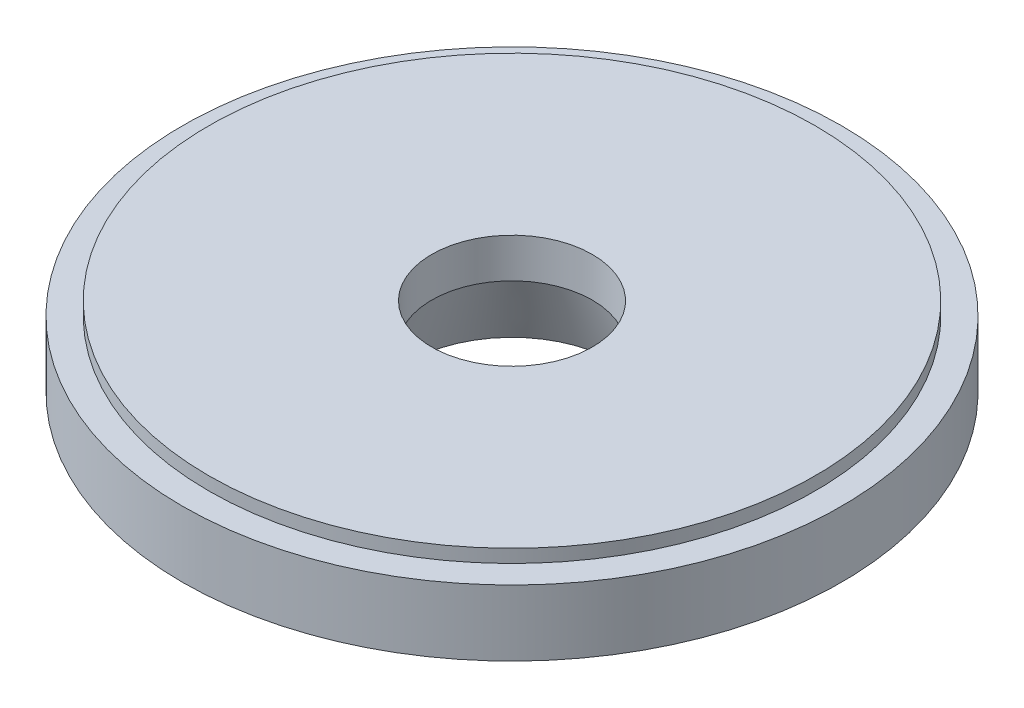
SolidWorks part; units mm, degrees
material "6061 Alloy"
ref_plane "Front Plane" through (0, 0, 0) normal (0, 0, 1) x (1, 0, 0)
ref_plane "Top Plane" through (0, 0, 0) normal (0, 1, 0) x (1, 0, 0)
ref_plane "Right Plane" through (0, 0, 0) normal (1, 0, 0) x (0, 0, -1)
sketch "Sketch1" plane through (0, 0, 0) normal (0, 1, 0) x (1, 0, 0)
  circle A0 centre (0, 0) radius 12.5
  dimension "D1" = 25
extrude "Boss-Extrude1" add sketch "Sketch1" along normal blind 2.5
shell "Shell1" thickness 1
sketch "Sketch2" plane through (0, 2.5, 0) normal (0, 1, 0) x (1, 0, 0)
  circle A1 centre (0, 0) radius 12.5 construction
  circle A2 centre (0, 0) radius 11.5
  circle A3 centre (0, 0) radius 11.5
  dimension "D1" = 1
extrude "Boss-Extrude2" add sketch "Sketch2" along normal blind 0.5
sketch "Sketch4" plane through (0, 0, 0) normal (0, 0, 1) x (1, 0, 0)
  line L0 (0, 3) -> (0, 0) construction
  line L1 (11.5, 3) -> (-11.5, 3) construction
  line L2 (4.4559, -1) -> (3.9559, -1)
  line L3 (3.9559, -1) -> (2.5, 3)
  line L4 (4.4559, -1) -> (3, 3)
  line L5 (3, 3) -> (2.5, 3)
  dimension "D1" = 110
  dimension "D2" = 0.5
  dimension "D3" = 4
  dimension "D4" = 2.5
revolve "Revolve1" add sketch "Sketch4" angle 360 about L0
sketch "Sketch5" plane through (0, 1.5, 0) normal (0, -1, 0) x (1, 0, 0)
  circle A1 centre (0, 0) radius 3.046
  circle A2 centre (0, 0) radius 3.046
  dimension "D1" = 0
extrude "Cut-Extrude3" cut sketch "Sketch5" against normal blind 10.5
